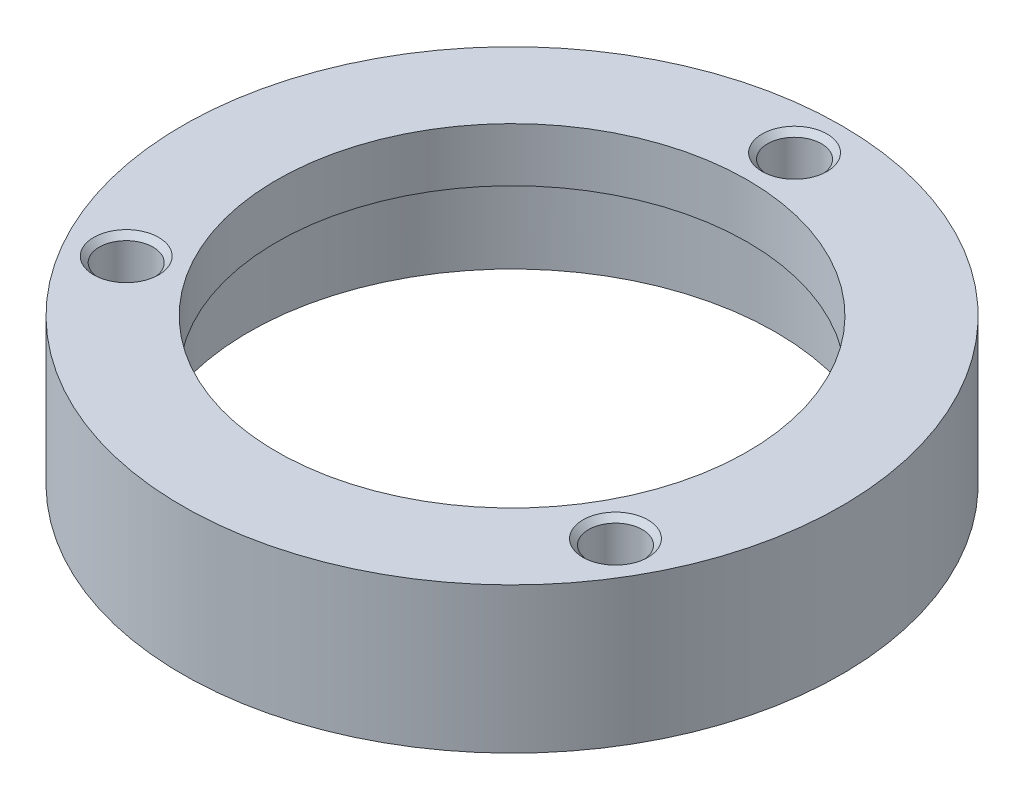
SolidWorks part; units mm, degrees
ref_plane "Front Plane" through (0, 0, 0) normal (0, 0, 1) x (1, 0, 0)
ref_plane "Top Plane" through (0, 0, 0) normal (0, 1, 0) x (1, 0, 0)
ref_plane "Right Plane" through (0, 0, 0) normal (1, 0, 0) x (0, 0, -1)
sketch "Sketch1" plane through (0, 0, 0) normal (0, 1, 0) x (1, 0, 0)
  circle A0 centre (0, 0) radius 21
  circle A1 centre (0, 0) radius 29.4
  circle A2 centre (0, 0) radius 29.25 construction
  dimension "D1" = 0.15
  dimension "D2" = 42
  dimension "D3" = 58.8
extrude "Boss-Extrude1" add sketch "Sketch1" along normal blind 13
sketch "Sketch2" plane through (0, 13, 0) normal (0, 1, 0) x (1, 0, 0)
  line L0 (0, 0) -> (0, 21) construction
  line L1 (0, 21) -> (0, 29.4) construction
  circle A0 centre (0, 25.2) radius 2.4
  circle A1 centre (0, 0) radius 21 construction
  circle A2 centre (0, 0) radius 29.4 construction
  circle A3 centre (21.8238, -12.6) radius 2.4
  circle A4 centre (-21.8238, -12.6) radius 2.4
  point P19 (0, 0)
  dimension "D2" = 4.8
  dimension "D1" = 25.2
  dimension "D3" = 3
extrude "Cut-Extrude1" cut sketch "Sketch2" against normal blind 4
chamfer "Chamfer1" distance 0.5 angle 45 3 edges at (-21.8238, 13, 15) (21.8238, 13, 15) (0, 13, -22.8)
sketch "Sketch4" plane through (0, 0, 0) normal (0, -1, 0) x (1, 0, 0)
  circle A0 centre (0, 0) radius 23.5
  dimension "D1" = 47
extrude "Cut-Extrude2" cut sketch "Sketch4" against normal offset from surface (8.2 mm away) 4.8 up to face at (-21.8238, 13, 15.5)
